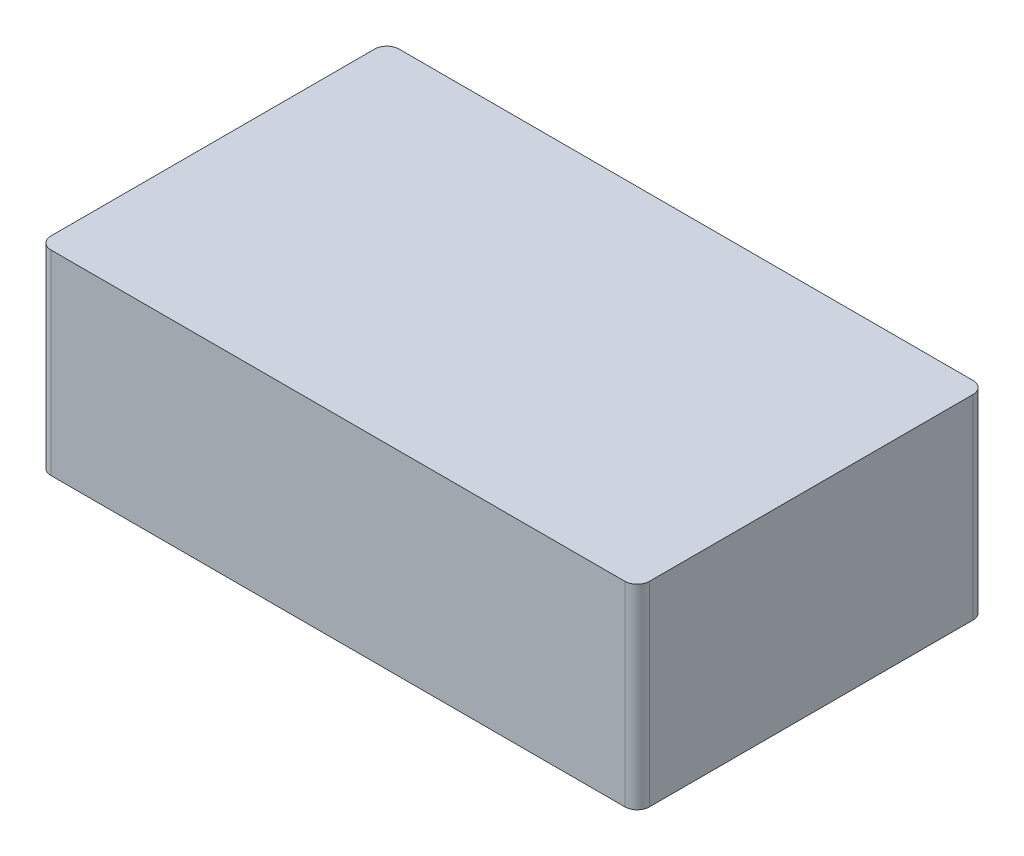
SolidWorks part; units mm, degrees
ref_plane "Front Plane" through (0, 0, 0) normal (0, 0, 1) x (1, 0, 0)
ref_plane "Top Plane" through (0, 0, 0) normal (0, 1, 0) x (1, 0, 0)
ref_plane "Right Plane" through (0, 0, 0) normal (1, 0, 0) x (0, 0, -1)
sketch "Sketch1" plane through (0, 0, 0) normal (0, 1, 0) x (1, 0, 0)
  line L1 (-24.5, -14.25) -> (24.5, -14.25)
  line L2 (-24.5, -14.25) -> (-24.5, 14.25)
  line L3 (-24.5, 14.25) -> (24.5, 14.25)
  line L4 (24.5, -14.25) -> (24.5, 14.25)
  line L5 (-24.5, -14.25) -> (24.5, 14.25) construction
  line L6 (-24.5, 14.25) -> (24.5, -14.25) construction
  point P0 (0, 0)
  dimension "D1" = 49
  dimension "D2" = 28.5
extrude "Boss-Extrude1" add sketch "Sketch1" along normal blind 16
fillet "Fillet1" radius 1 4 edges at (-24.5, 8, -14.25) (24.5, 8, -14.25) (24.5, 8, 14.25) (-24.5, 8, 14.25)
